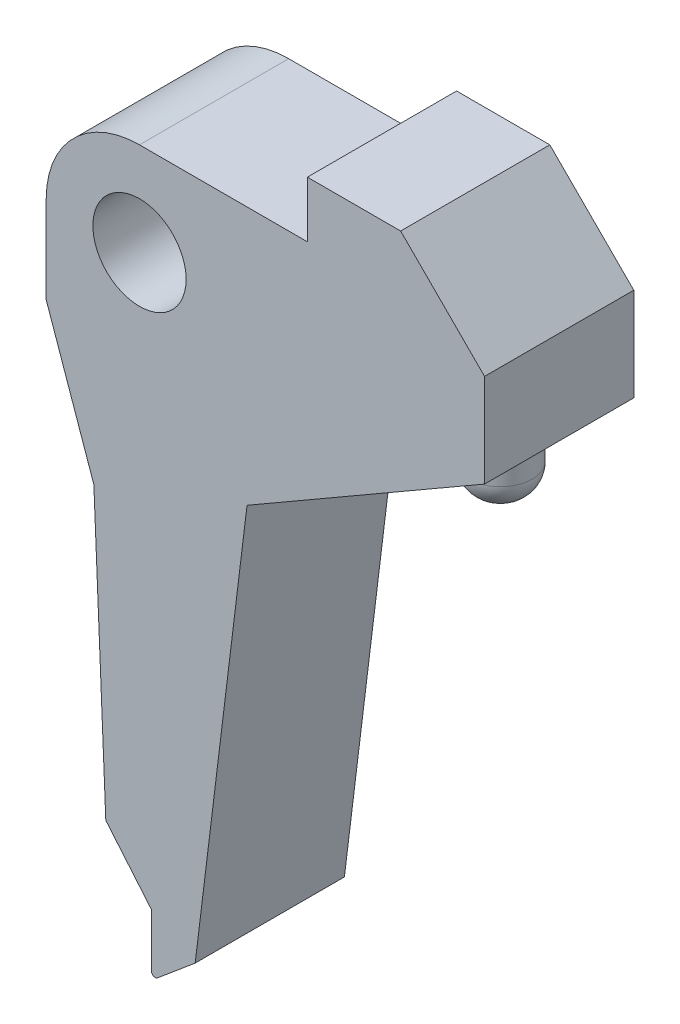
SolidWorks part; units mm, degrees
ref_plane "정면" through (0, 0, 0) normal (0, 0, 1) x (1, 0, 0)
ref_plane "윗면" through (0, 0, 0) normal (0, 1, 0) x (1, 0, 0)
ref_plane "우측면" through (0, 0, 0) normal (1, 0, 0) x (0, 0, -1)
sketch "스케치1" plane through (0, 0, 0) normal (0, 0, 1) x (1, 0, 0)
  line L0 (0, 5) -> (9, 5)
  line L1 (9, 5) -> (9, 8)
  line L2 (9, 8) -> (14, 8)
  line L3 (14, 8) -> (18.5, 3.5)
  line L4 (18.5, 3.5) -> (18.5, -1.5)
  line L5 (18.5, -1.5) -> (12.1331, -5.1759)
  line L6 (4.5008, -19.1586) -> (2.9854, -31.5)
  line L7 (2.9854, -31.5) -> (0.9682, -33.193)
  line L8 (0.6396, -33.0398) -> (0.6396, -30.1837)
  line L9 (0.6396, -30.1837) -> (-1.8057, -27.2695)
  line L10 (-1.8057, -27.2695) -> (-2.4456, -12)
  line L11 (-2.4456, -12) -> (-5, -4.6966)
  line L12 (-5, -4.6966) -> (-5, 0)
  line L13 (18.5, -1.5) -> (3.5201, -1.5) construction
  line L14 (2.9854, -31.5) -> (2.9854, -0.7863) construction
  line L15 (18.5, 3.5) -> (6.1947, 3.5) construction
  line L16 (-1.8057, -27.2695) -> (1.5473, -27.2695) construction
  line L19 (4.5008, -19.1586) -> (5.7663, -8.8518)
  line L20 (5.7663, -8.8518) -> (12.1331, -5.1759)
  circle A0 centre (0, 0) radius 2.5
  arc A1 (0, 5) -> (-5, 0) centre (0, 0) ccw
  arc A2 (0.9682, -33.193) -> (0.6396, -33.0398) centre (0.8396, -33.0398) cw
  dimension "D1" = 5
  dimension "D2" = 10
  dimension "D3" = 0.2
  dimension "D5" = 9
  dimension "D6" = 5
  dimension "D7" = 5
  dimension "D8" = 30
  dimension "D9" = 7
  dimension "D11" = 45
  dimension "D13" = 50
  dimension "D14" = 12
  dimension "D15" = 3
  dimension "D16" = 4.5
extrude "보스-돌출1" add sketch "스케치1" along normal blind 8
ref_plane "평면1" through (0, -1.5, 0) normal (0, 1, 0) x (1, 0, 0)
sketch "스케치3" plane through (0, -1.5, 0) normal (0, 1, 0) x (1, 0, 0)
  line L1 (18.5, -4) -> (12.1992, -4) construction
  line L3 (18.5, -8) -> (18.5, 0) construction
  line L4 (5.8984, -8) -> (18.5, 0) construction
  circle A0 centre (15.3496, -4) radius 2.5
  dimension "D1" = 5
extrude "컷-돌출1" cut sketch "스케치3" against normal up to next
sketch "스케치4" plane through (0, -1.5, 0) normal (0, -1, 0) x (1, 0, 0)
  circle A0 centre (15.3496, 4) radius 1.7
  dimension "D1" = 3.4
extrude "보스-돌출2" add sketch "스케치4" along normal blind 4
fillet "필렛1" radius 1.5 1 edges at (15.3496, -5.5, 2.3)
